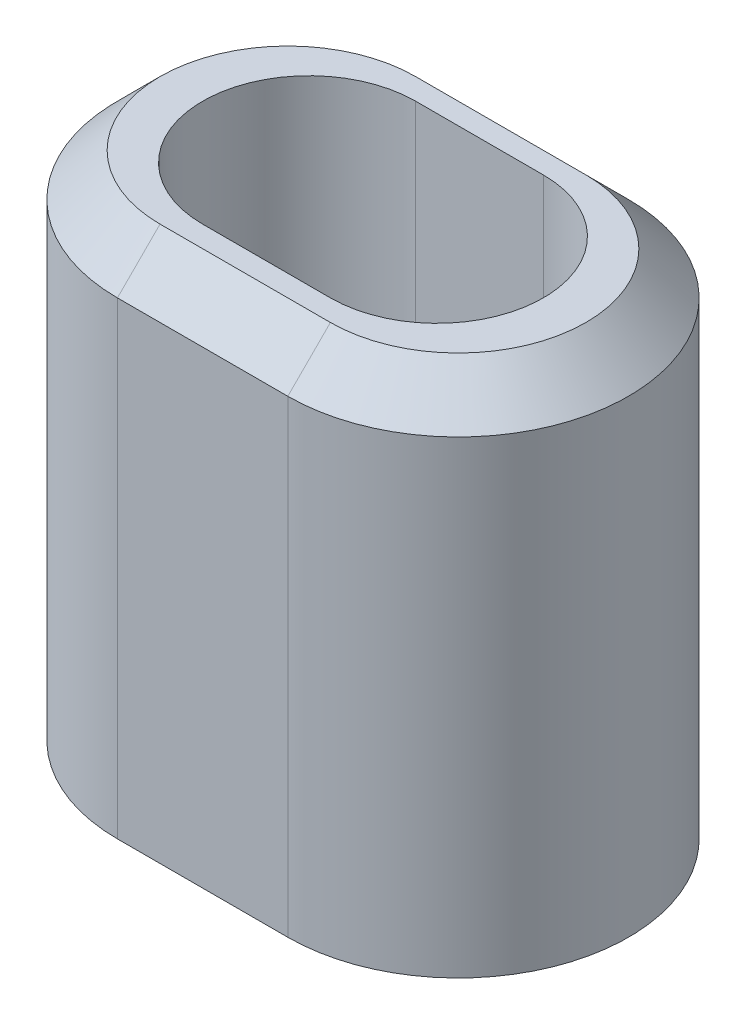
SolidWorks part; units mm, degrees
ref_plane "Alzado" through (0, 0, 0) normal (0, 0, 1) x (1, 0, 0)
ref_plane "Planta" through (0, 0, 0) normal (0, 1, 0) x (1, 0, 0)
ref_plane "Vista lateral" through (0, 0, 0) normal (1, 0, 0) x (0, 0, -1)
sketch "Croquis1" plane through (0, 0, 0) normal (0, 1, 0) x (1, 0, 0)
  line L0 (0, 0) -> (-20, 0) construction
  line L7 (0, -20) -> (-20, -20)
  line L8 (0, 20) -> (-20, 20)
  line L9 (-2.5, 0) -> (-17.5, 0) construction
  line L10 (-2.5, -12.5) -> (-17.5, -12.5)
  line L11 (-2.5, 12.5) -> (-17.5, 12.5)
  arc A6 (0, -20) -> (0, 20) centre (0, 0) ccw
  arc A7 (-20, 20) -> (-20, -20) centre (-20, 0) ccw
  arc A8 (-2.5, -12.5) -> (-2.5, 12.5) centre (-2.5, 0) ccw
  arc A9 (-17.5, 12.5) -> (-17.5, -12.5) centre (-17.5, 0) ccw
  point P3 (-10, 0)
  point P8 (-40, 0)
  point P9 (20, 0)
  point P10 (-10, 0)
  point P17 (-30, 0)
  point P18 (10, 0)
  point P19 (0, 0)
  dimension "D1" = 20
  dimension "D2" = 60
  dimension "D3" = 40
  dimension "D4" = 25
extrude "Saliente-Extruir1" add sketch "Croquis1" along normal blind 60
chamfer "Chaflán1" distance 5 angle 45 4 edges at (-40, 60, 0) (-10, 60, -20) (20, 60, 0) (-10, 60, 20)
